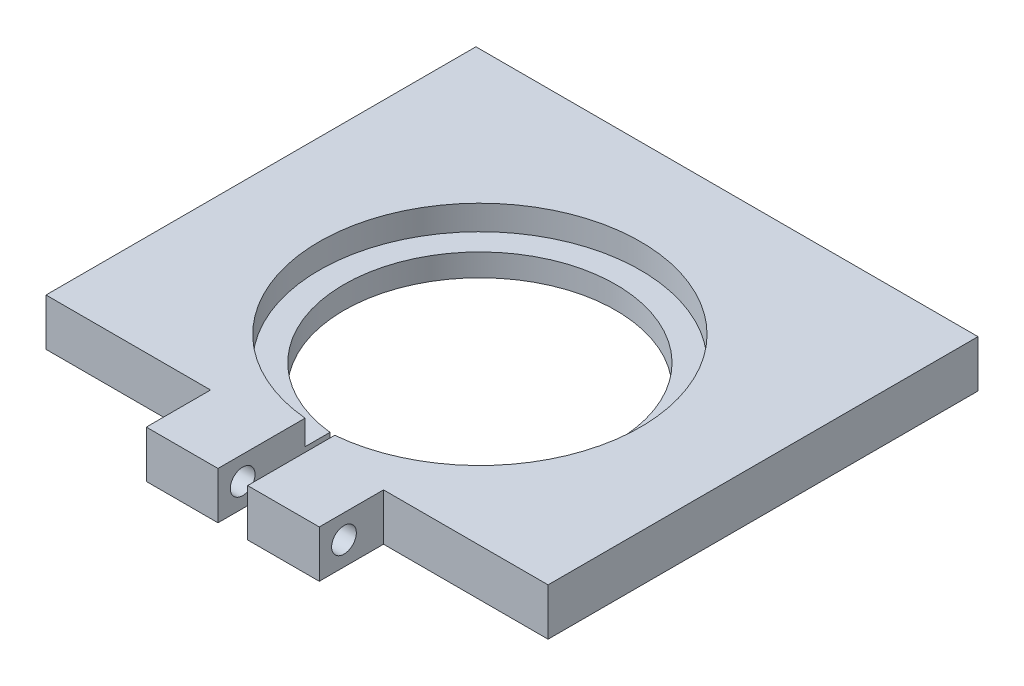
SolidWorks part; units mm, degrees
ref_plane "Plano frontal" through (0, 0, 0) normal (0, 0, 1) x (1, 0, 0)
ref_plane "Plano superior" through (0, 0, 0) normal (0, 1, 0) x (1, 0, 0)
ref_plane "Plano direito" through (0, 0, 0) normal (1, 0, 0) x (0, 0, -1)
sketch "Esboço1" plane through (0, 0, 0) normal (0, 1, 0) x (1, 0, 0)
  line L0 (50.8, 50) -> (-50.8, -50) construction
  line L1 (-50.8, 50) -> (50.8, 50)
  line L2 (-50.8, 50) -> (-50.8, -50)
  line L3 (-50.8, -50) -> (50.8, -50)
  line L4 (50.8, 50) -> (50.8, -50)
  dimension "D1" = 101.6
  dimension "D2" = 100
extrude "Ressalto-extrusão1" add sketch "Esboço1" along normal blind 9.53 contours L2 L3 L4 L1
sketch "Esboço2" plane through (0, 0, -50) normal (0, 0, -1) x (-1, 0, 0)
  circle A0 centre (-45.8, 4.76) radius 2.6
  circle A1 centre (-22.8, 4.76) radius 2.6
  circle A2 centre (22.8, 4.76) radius 2.6
  circle A3 centre (45.8, 4.76) radius 2.6
extrude "Corte-extrusão1" cut sketch "Esboço2" against normal blind 20
sketch "Esboço3" plane through (0, 9.53, 0) normal (0, 1, 0) x (1, 0, 0)
  line L0 (-50.8, -50) -> (50.8, -50) construction
  line L1 (50.8, 50) -> (50.8, -50) construction
  circle A0 centre (0, 0) radius 32.51
  dimension "D1" = 65.02
  dimension "D2" = 50
  dimension "D3" = 50.8
extrude "Corte-extrusão2" cut sketch "Esboço3" against normal blind 5
sketch "Esboço4" plane through (0, 4.53, 0) normal (0, 1, 0) x (1, 0, 0)
  circle A0 centre (0, 0) radius 27.5
  dimension "D1" = 55
extrude "Corte-extrusão3" cut sketch "Esboço4" against normal up to next
sketch "Esboço5" plane through (0, 9.53, 0) normal (0, 1, 0) x (1, 0, 0)
  line L0 (0, -50) -> (0, -37.4552) construction
  line L1 (50.8, -50) -> (17.5, -50)
  line L2 (50.8, -50) -> (50.8, -37)
  line L3 (50.8, -37) -> (17.5, -37)
  line L4 (17.5, -50) -> (17.5, -37)
  line L5 (-50.8, -50) -> (-17.5, -50)
  line L6 (-50.8, -50) -> (-50.8, -37)
  line L7 (-50.8, -37) -> (-17.5, -37)
  line L8 (-17.5, -50) -> (-17.5, -37)
  line L9 (-50.8, -50) -> (50.8, -50) construction
  dimension "D1" = 17.5
  dimension "D2" = 17.5
  dimension "D3" = 13
  dimension "D4" = 13
extrude "Corte-extrusão4" cut sketch "Esboço5" against normal up to next
sketch "Esboço6" plane through (0, 9.53, 0) normal (0, 1, 0) x (1, 0, 0)
  line L1 (0, 0) -> (0, -50) construction
  line L2 (-17.5, -50) -> (17.5, -50) construction
  line L3 (3, -50) -> (-3, -50)
  line L4 (3, -50) -> (3, -20.3326)
  line L5 (3, -20.3326) -> (-3, -20.3326)
  line L6 (-3, -50) -> (-3, -20.3326)
  dimension "D1" = 3
  dimension "D2" = 3
extrude "Corte-extrusão5" cut sketch "Esboço6" against normal up to next
sketch "Esboço7" plane through (-17.5, 0, 0) normal (-1, 0, 0) x (0, 0, 1)
  line L0 (50, 9.53) -> (40, 0) construction
  line L1 (50, 0) -> (37, 0) construction
  circle A0 centre (45, 4.765) radius 2.5
  dimension "D2" = 5
  dimension "D1" = 10
extrude "Corte-extrusão6" cut sketch "Esboço7" against normal up to surface (35 mm away) up to face at (17.5, 4.765, 43.5)
